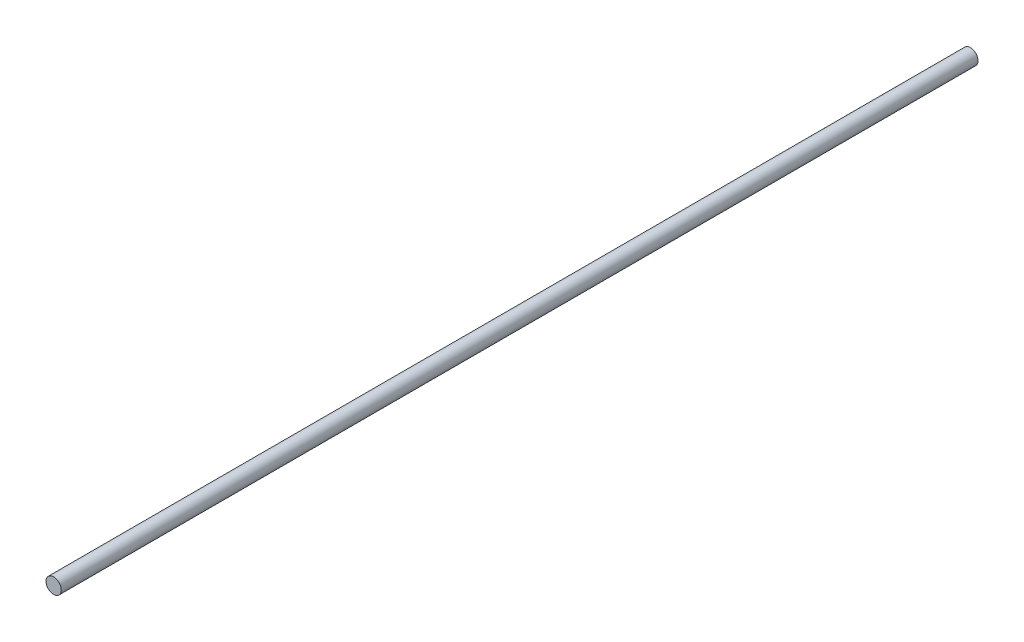
SolidWorks part; units mm, degrees
ref_plane "Front Plane" through (0, 0, 0) normal (0, 0, 1) x (1, 0, 0)
ref_plane "Top Plane" through (0, 0, 0) normal (0, 1, 0) x (1, 0, 0)
ref_plane "Right Plane" through (0, 0, 0) normal (1, 0, 0) x (0, 0, -1)
sketch "Sketch1" plane through (0, 0, 0) normal (0, 0, 1) x (1, 0, 0)
  circle A0 centre (0, 0) radius 3.175
  dimension "D1" = 6.35
extrude "Boss-Extrude1" add sketch "Sketch1" along normal blind 381
